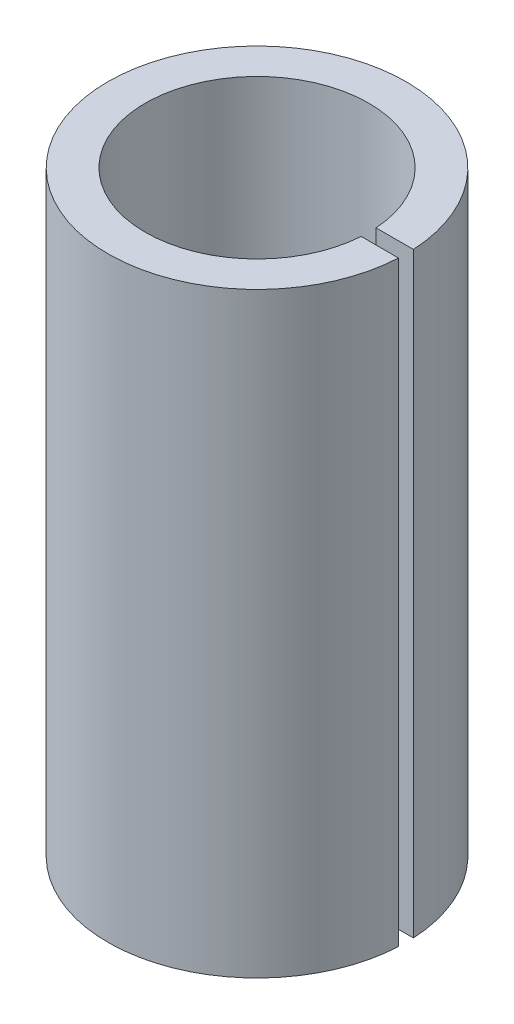
SolidWorks part; units mm, degrees
ref_plane "Front Plane" through (0, 0, 0) normal (0, 0, 1) x (1, 0, 0)
ref_plane "Top Plane" through (0, 0, 0) normal (0, 1, 0) x (1, 0, 0)
ref_plane "Right Plane" through (0, 0, 0) normal (1, 0, 0) x (0, 0, -1)
ref_plane "Plane1" through (0, 0, 0) normal (0, 0, 1) x (1, 0, 0)
sketch "Sketch1" plane through (0, 0, 0) normal (0, 0, 1) x (1, 0, 0)
  line L0 (1.5, 0) -> (2, 0)
  line L1 (2, 0) -> (2, 8)
  line L2 (2, 8) -> (1.5, 8)
  line L3 (1.5, 8) -> (1.5, 0)
  line L4 (0, 0) -> (0, 8) construction
revolve "Revolve1" add sketch "Sketch1" angle 360 about L4
ref_plane "Plane2" through (0, 0, 0) normal (1, 0, 0) x (0, 0, -1)
sketch "Sketch2" plane through (0, 0, 0) normal (1, 0, 0) x (0, 0, -1)
  line L0 (-0.1, 0) -> (0.1, 0)
  line L1 (0.1, 0) -> (0.1, 8)
  line L2 (0.1, 8) -> (-0.1, 8)
  line L3 (-0.1, 8) -> (-0.1, 0)
extrude "Cut-Extrude1" cut sketch "Sketch2" along normal blind 4
